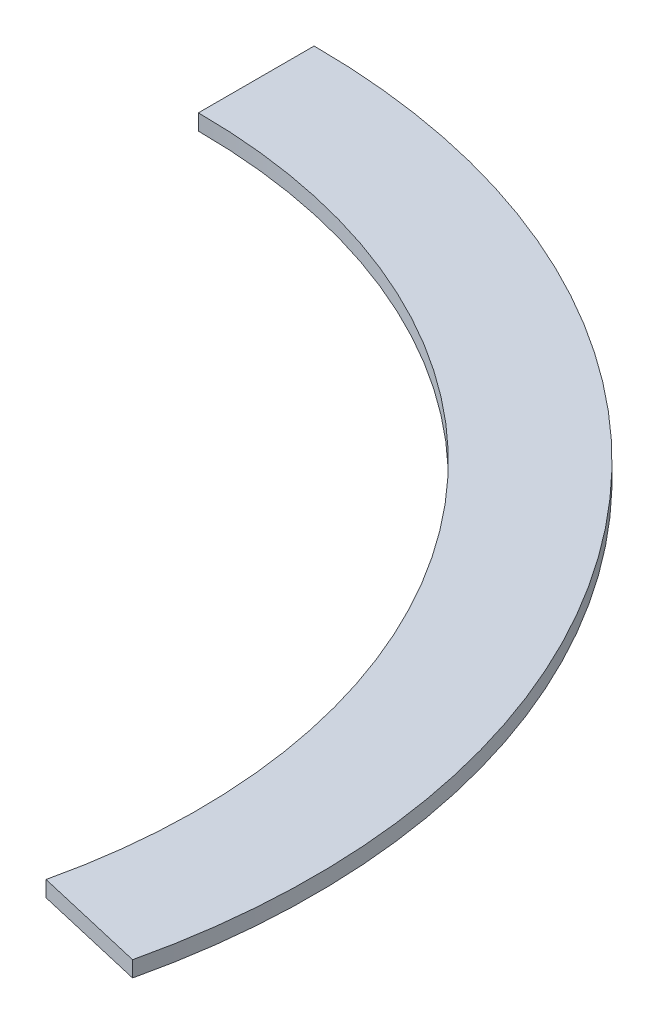
SolidWorks part; units mm, degrees
ref_plane "Front Plane" through (0, 0, 0) normal (0, 0, 1) x (1, 0, 0)
ref_plane "Top Plane" through (0, 0, 0) normal (0, 1, 0) x (1, 0, 0)
ref_plane "Right Plane" through (0, 0, 0) normal (1, 0, 0) x (0, 0, -1)
sketch "Sketch1" plane through (0, 0, 0) normal (0, 1, 0) x (1, 0, 0)
  line L0 (0, 38.0919) -> (0, 45.3978)
  line L1 (37.1023, -8.6262) -> (44.2184, -10.2807)
  arc A0 (0, 38.0919) -> (37.1023, -8.6262) centre (0, 0) cw
  arc A1 (0, 45.3978) -> (44.2184, -10.2807) centre (0, 0) cw
  dimension "D3" = 7.306
  dimension "D4" = 45.3978
  dimension "D1" = 68.5363
  dimension "D2" = 81.6814
extrude "Boss-Extrude1" add sketch "Sketch1" along normal blind 1
equation "\"outer_diameter\"= 26mm"
equation "\"D2@Sketch1\"= \"outer_diameter\" * pi"
equation "\"inner diameter\" = 21.815774mm"
equation "\"D1@Sketch1\"= \"inner diameter\" * pi"
equation "\"D4@Sketch1\" = \"outer_diameter\" / ( 2 * sin ( 16.64 ) )"
equation "\"height\" = 7mm"
equation "\"D3@Sketch1\"= \"height\" / cos ( 16.64 )"
